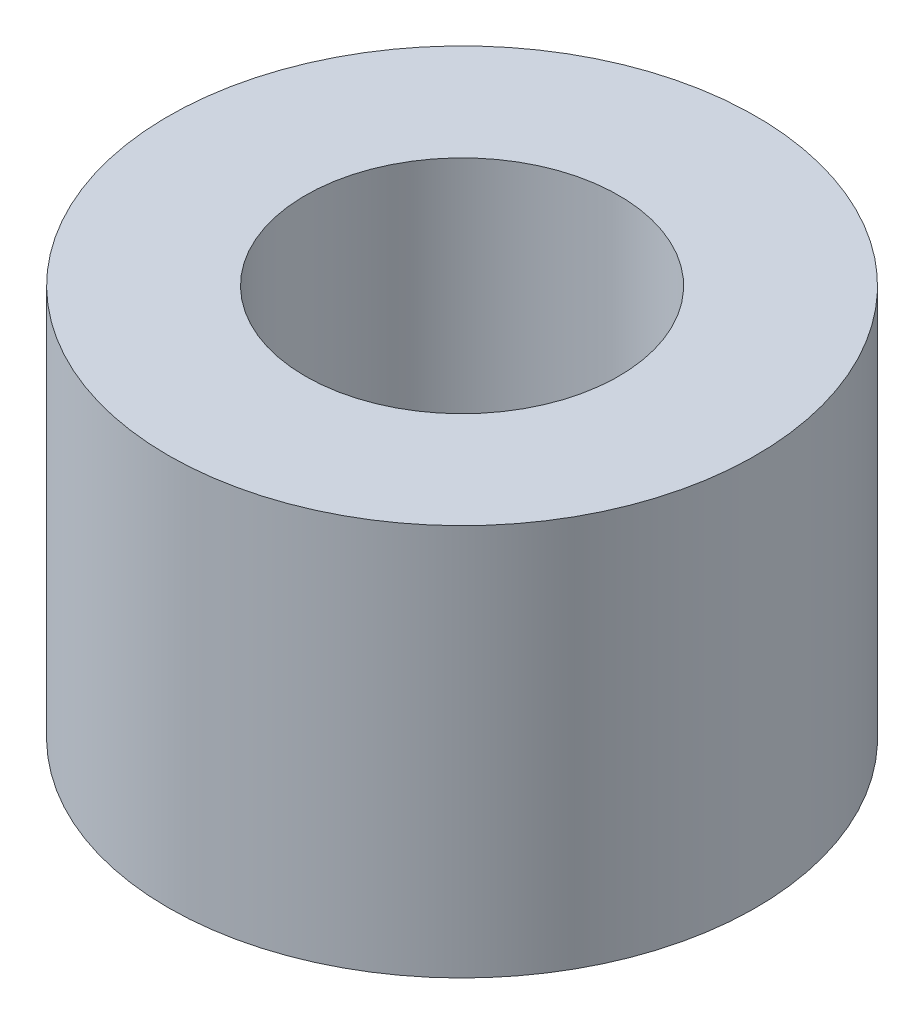
SolidWorks part; units mm, degrees
ref_plane "Front Plane" through (0, 0, 0) normal (0, 0, 1) x (1, 0, 0)
ref_plane "Top Plane" through (0, 0, 0) normal (0, 1, 0) x (1, 0, 0)
ref_plane "Right Plane" through (0, 0, 0) normal (1, 0, 0) x (0, 0, -1)
sketch "Sketch1" plane through (0, 0, 0) normal (0, 1, 0) x (1, 0, 0)
  circle A0 centre (0, 0) radius 1.6
  circle A1 centre (0, 0) radius 3
  dimension "D1" = 3.2
  dimension "D2" = 6
extrude "Boss-Extrude1" add sketch "Sketch1" along normal blind 4
